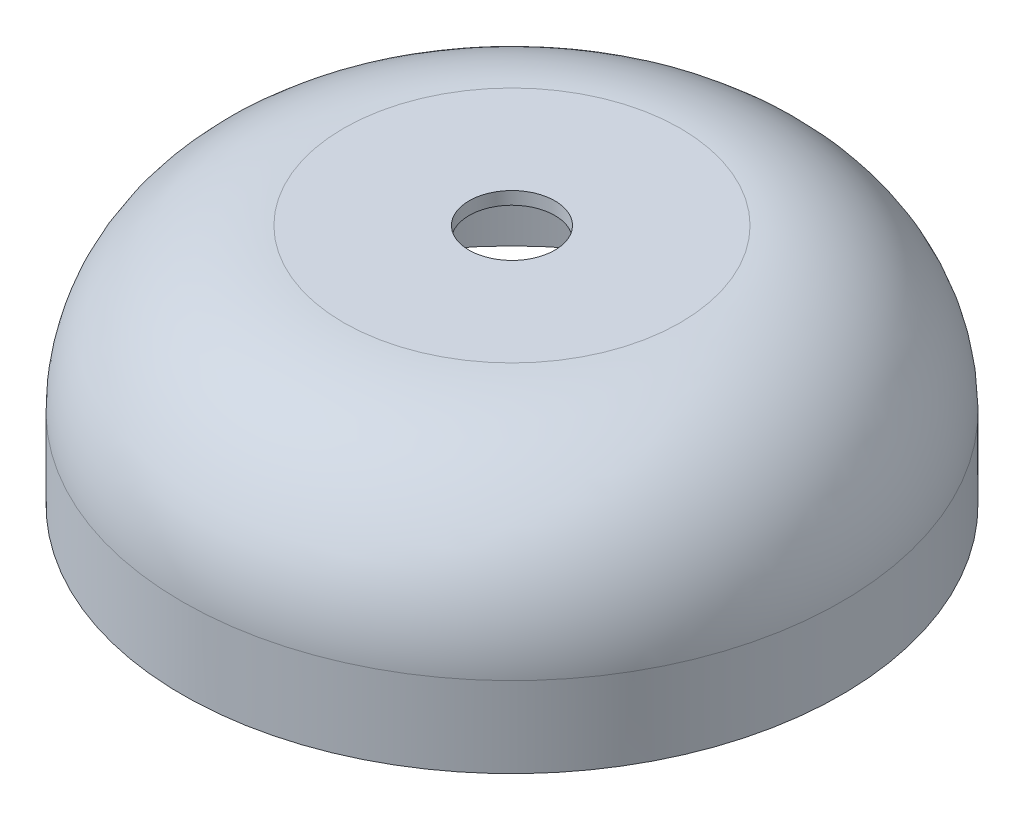
SolidWorks part; units mm, degrees
ref_plane "Front Plane" through (0, 0, 0) normal (0, 0, 1) x (1, 0, 0)
ref_plane "Top Plane" through (0, 0, 0) normal (0, 1, 0) x (1, 0, 0)
ref_plane "Right Plane" through (0, 0, 0) normal (1, 0, 0) x (0, 0, -1)
sketch "Sketch1" plane through (0, 0, 0) normal (0, 1, 0) x (1, 0, 0)
  circle A0 centre (0, 0) radius 38.85
  dimension "D1" = 77.7
extrude "Boss-Extrude1" add sketch "Sketch1" along normal blind 28.5
fillet "Fillet1" radius 19 1 edges at (0, 28.5, 38.85)
shell "Shell1" thickness 1.5
sketch "Sketch3" plane through (0, 28.5, 0) normal (0, 1, 0) x (1, 0, 0)
  circle A0 centre (0, 0) radius 5.05
  dimension "10.1" = 10.1
extrude "Cut-Extrude1" cut sketch "Sketch3" against normal through all
